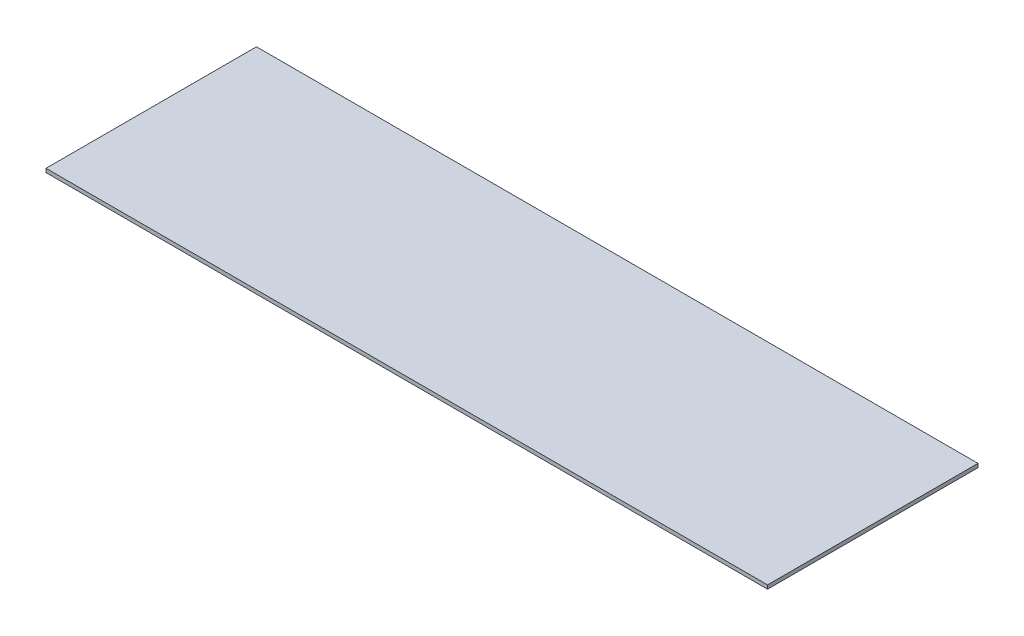
SolidWorks part; units mm, degrees
ref_plane "Front Plane" through (0, 0, 0) normal (0, 0, 1) x (1, 0, 0)
ref_plane "Top Plane" through (0, 0, 0) normal (0, 1, 0) x (1, 0, 0)
ref_plane "Right Plane" through (0, 0, 0) normal (1, 0, 0) x (0, 0, -1)
sketch "Sketch1" plane through (0, 0, 0) normal (0, 1, 0) x (1, 0, 0)
  line L1 (-1219.2, -355.6) -> (1219.2, -355.6)
  line L2 (-1219.2, -355.6) -> (-1219.2, 355.6)
  line L3 (-1219.2, 355.6) -> (1219.2, 355.6)
  line L4 (1219.2, -355.6) -> (1219.2, 355.6)
  line L5 (-1219.2, -355.6) -> (1219.2, 355.6) construction
  line L6 (-1219.2, 355.6) -> (1219.2, -355.6) construction
  point P0 (0, 0)
  dimension "D1" = 711.2
  dimension "D2" = 2438.4
extrude "Boss-Extrude1" add sketch "Sketch1" along normal blind 12.7
equation "\"narrow\"=28"
equation "\"wide\"= 83 / 2"
